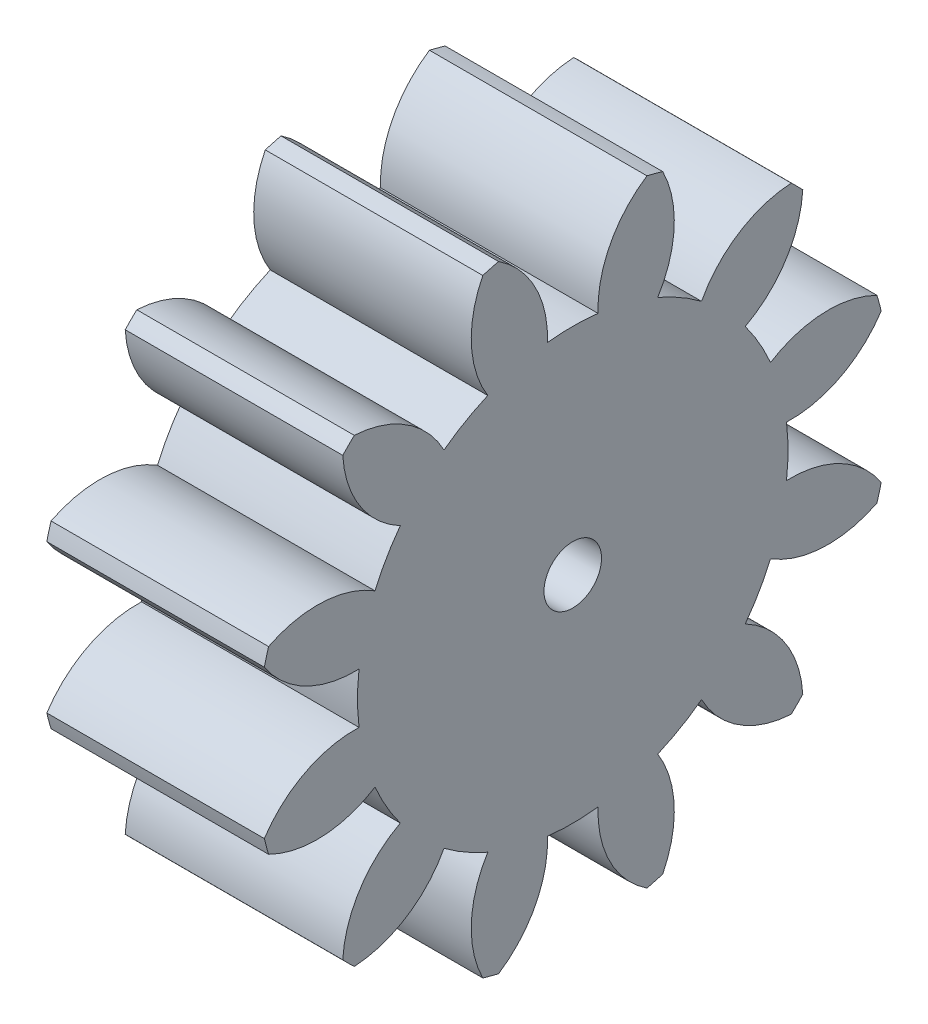
SolidWorks part; units mm, degrees
ref_plane "Plane1" through (0, 0, 0) normal (0, 0, 1) x (1, 0, 0)
ref_plane "Plane2" through (0, 0, 0) normal (0, 1, 0) x (1, 0, 0)
ref_plane "Plane3" through (0, 0, 0) normal (1, 0, 0) x (0, 0, -1)
other "Configuration Table"
sketch "HoldingSke" plane through (0, 0, 0) normal (0, 1, 0) x (1, 0, 0)
  line L0 (0, 0) -> (0.3913, -0.0832)
  line L1 (-15, 0) -> (100, 0) construction
  line L2 (0, 0) -> (-2.1039, 2.3779)
  line L3 (0, 0) -> (-11.863, 4.5341)
  line L4 (0, 0) -> (8.4473, 1.7955)
  line L5 (0, 0) -> (-46.8476, -17.4728)
  line L6 (0, 0) -> (-9.9476, -6.7116)
  line L7 (-2.1039, 2.3779) -> (8.6586, 51.2059)
  line L8 (-76.2, 54.61) -> (-75.7, 54.61)
  line L9 (-71.009, 38.7566) -> (-53.1078, 45.2721)
  line L10 (-76.2, 71.12) -> (104.1128, 71.12)
  line L11 (0, 0) -> (-12, 0)
  line L12 (-76.2, 101.6) -> (-76.113, 101.6)
  line L13 (24.9733, 27.94) -> (52.9518, 28.4284)
  line L14 (24.9733, 27.94) -> (24.9743, 27.94)
  line L15 (24.9733, 27.94) -> (100.4006, 29.5858)
  line L16 (-63.627, -2.5) -> (-12.827, -2.5)
  circle A0 centre (0, 0) radius 1.5
  circle A1 centre (0, 0) radius 11.874
  circle A2 centre (0, 0) radius 37.5
  circle A3 centre (0, 0) radius 1.5
  dimension "MHD" = 23.748
  dimension "Hub_dia" = 75
  dimension "Bore" = 3
  dimension "MBD" = 3
  dimension "Num_teeth" = 12
  dimension "Pitch" = 0.4
  dimension "Overall_len" = 50
  dimension "Show_teeth" = 12
  dimension "Thickness" = 12
  dimension "OAL" = 50.0001
  dimension "T_dim" = 0.5
  dimension "Ap" = 20
  dimension "H" = 19.05
  dimension "Pitch_radius" = 180.3128
  dimension "Width" = 12
  dimension "Backlash" = 0.087
  dimension "Addendum_fac" = 1
  dimension "Dedendum_fac" = 1.25
  dimension "Clearance_fac" = 0.25
  dimension "Dedendum_add" = 0.001
  dimension "Module" = 2.5
sketch "BasProSke" plane through (0, 0, 0) normal (0, 1, 0) x (1, 0, 0)
  line L0 (-10, 0) -> (60, 0) construction
  line L1 (0, 0) -> (0, 17.5)
  line L2 (0, 0) -> (12, 0)
  line L3 (12, 0) -> (12, 17.5)
  line L4 (12, 17.5) -> (0, 17.5)
  dimension "Thickness" = 12
  dimension "Diameter" = 35
revolve "Base-Revolve" add sketch "BasProSke" angle 360 about L0
sketch "TooCutSke" plane through (0, 0, 0) normal (1, 0, 0) x (0, 0, -1)
  line L1 (0, 0) -> (0, 107) construction
  line L2 (0, 0) -> (-2.1099, 14.8509) construction
  line L3 (0, 0) -> (-7.7081, 28.7671) construction
  line L4 (-2.1099, 14.8509) -> (-3.8541, 14.3835) construction
  arc A0 (1.3944, 11.7918) -> (-1.3944, 11.7918) centre (0, 0) ccw
  arc A1 (4.1219, 17.0338) -> (-4.1219, 17.0338) centre (0, 0) ccw
  circle A2 centre (0, 0) radius 15 construction
  circle A3 centre (0, 0) radius 14.0954 construction
  arc A4 (-1.3944, 11.7918) -> (-4.1219, 17.0338) centre (-7.3907, 12.0024) ccw
  arc A5 (4.1219, 17.0338) -> (1.3944, 11.7918) centre (7.3907, 12.0024) ccw
  dimension "Root_dia" = 23.748
  dimension "Overcut_dia" = 35.0508
  dimension "Pitch_dia" = 30
  dimension "Base_dia" = 28.1908
  dimension "Flank_rad" = 6
  dimension "Half_ang" = 15
  dimension "Half_CT" = 1.8056
extrude "ToothCut" cut sketch "TooCutSke" along normal through all
fillet "Breaks" [suppressed] radius 0.05
fillet "RootFillets" [suppressed] radius 0.626
pattern_circular "TeethCuts" count 12 every 30 about axis through (-10, 0, 0) along (1, 0, 0) of "ToothCut", "RootFillets", "Breaks"
sketch "HubNeaOneSke" plane through (0, 0, 0) normal (-1, 0, 0) x (0, 0, 1)
  circle A0 centre (0, 0) radius 11.874
  dimension "Diameter" = 23.748
extrude "HubNearOne" [suppressed] add sketch "HubNeaOneSke" along normal blind 38.0001
sketch "HubNeaBotSke" plane through (0, 0, 0) normal (-1, 0, 0) x (0, 0, 1)
  circle A0 centre (0, 0) radius 11.874
  dimension "Diameter" = 23.748
extrude "HubNearBoth" [suppressed] add sketch "HubNeaBotSke" along normal blind 19
ref_plane "FarPln" through (12, 0, 0) normal (1, 0, 0) x (0, 0, -1)
sketch "HubFarSke" plane through (12, 0, 0) normal (1, 0, 0) x (0, 0, -1)
  circle A0 centre (0, 0) radius 11.874
  dimension "Diameter" = 23.748
extrude "HubFar" [suppressed] add sketch "HubFarSke" along normal blind 19
sketch "BorSke" plane through (0, 0, 0) normal (1, 0, 0) x (0, 0, -1)
  circle A0 centre (0, 0) radius 1.5
  dimension "Diameter" = 3
extrude "Bore" cut sketch "BorSke" along normal mid plane 100.0001
sketch "KeySke" plane through (0, 0, 0) normal (1, 0, 0) x (0, 0, -1)
  line L0 (-0.6, 0) -> (-0.6, 2)
  line L1 (-0.6, 2) -> (0.6, 2)
  line L2 (0.6, 2) -> (0.6, 0)
  line L3 (0, 0) -> (0, 34) construction
  line L4 (-0.6, 0) -> (0.6, 0)
  dimension "Offset" = 2
extrude "Keyway" [suppressed] cut sketch "KeySke" along normal mid plane 100.0001
pattern_circular "Keyway2" [suppressed] count 2 every 90 about axis through (-10, 0, 0) along (1, 0, 0)
sketch "Croquis1" plane through (0, 0, 0) normal (-1, 0, 0) x (0, 0, 1)
  circle A0 centre (0, 0) radius 1.5875
  dimension "D1" = 3.175
extrude "Cortar-Extruir1" cut sketch "Croquis1" against normal through all
equation "' \"Module@HoldingSke\" = 6.35"
equation "' \"Num_teeth@HoldingSke\" = 12"
equation "' \"Ap@HoldingSke\" =  20"
equation "' \"Ap@HoldingSke\" = 20"
equation "' \"Width@HoldingSke\" = 0.5 * 25.4"
equation "' \"Hub_dia@HoldingSke\"= 1 * 25.4"
equation "' \"Hub_dia@HoldingSke\" = 1 * 25.4"
equation "' \"Overall_len@HoldingSke\" = 1.0 * 25.4"
equation "' \"Bore@HoldingSke\" = 0.75 * 25.4"
equation "' \"T_dim@HoldingSke\" = 0.1 * 25.4"
equation "' \"Width@KeySke\" = 0.25 * 25.4"
equation "' \"Show_teeth@HoldingSke\" = 13"
equation "' \"Backlash@HoldingSke\" = 0.009 * 25.4"
equation "' \"Addendum_fac@HoldingSke\" = 1.0"
equation "' \"Dedendum_fac@HoldingSke\" = 1.25"
equation "' \"Dedendum_add@HoldingSke\" = 0.00005 * 25.4"
equation "' \"Clearance_fac@HoldingSke\" = 0.25"
equation "\"Pitch@HoldingSke\" = 1 / \"Module@HoldingSke\""
equation "\"Overcut_dia@TooCutSke\" = (\"Num_teeth@HoldingSke\" + 2 * \"Addendum_fac@HoldingSke\") / \"Pitch@HoldingSke\" + 0.002 * 25.4"
equation "\"Pitch_dia@TooCutSke\" = \"Num_teeth@HoldingSke\" / \"Pitch@HoldingSke\""
equation "\"Base_dia@TooCutSke\" = \"Num_teeth@HoldingSke\" / \"Pitch@HoldingSke\" * cos((\"Ap@HoldingSke\"  * 3.14159265 / 180))"
equation "\"Root_dia@TooCutSke\" = (\"Num_teeth@HoldingSke\" + 2) / \"Pitch@HoldingSke\" - 2 * (\"Addendum_fac@HoldingSke\" + \"Dedendum_fac@HoldingSke\") / \"Pitch@HoldingSke\" - \"Dedendum_add@HoldingSke\" * 2"
equation "\"Half_ang@TooCutSke\" = 180 / \"Num_teeth@HoldingSke\""
equation "\"Half_CT@TooCutSke\" = \"Num_teeth@HoldingSke\" / \"Pitch@HoldingSke\" * sin((3.14159265 / 2 / \"Num_teeth@HoldingSke\")) / 2 - 7 * \"Backlash@HoldingSke\" / 4"
equation "\"Flank_rad@TooCutSke\" = \"Num_teeth@HoldingSke\" / \"Pitch@HoldingSke\" / 5"
equation "\"Radius@RootFillets\" = \"Clearance_fac@HoldingSke\" / \"Pitch@HoldingSke\" + \"Dedendum_add@HoldingSke\""
equation "\"Break_rad@Breaks\" = 0.02 / \"Pitch@HoldingSke\""
equation "\"Thickness@HoldingSke\" = \"Width@HoldingSke\""
equation "\"OAL@HoldingSke\" = \"Thickness@HoldingSke\""
equation "\"MHD@HoldingSke\" = (\"Num_teeth@HoldingSke\" + 2) / \"Pitch@HoldingSke\" - 2 * (\"Addendum_fac@HoldingSke\" + \"Dedendum_fac@HoldingSke\")  / \"Pitch@HoldingSke\" - \"Dedendum_add@HoldingSke\" * 2"
equation "\"MBD@HoldingSke\" = (\"Num_teeth@HoldingSke\" + 2) / \"Pitch@HoldingSke\" - 2 * (\"Addendum_fac@HoldingSke\" + \"Dedendum_fac@HoldingSke\")  / \"Pitch@HoldingSke\" - \"Dedendum_add@HoldingSke\" * 2 - 0.002 * 25.4"
equation "\"MHD@HoldingSke\" = ((sgn( \"MHD@HoldingSke\" - \"Hub_dia@HoldingSke\" )-1)*( \"MHD@HoldingSke\" - \"Hub_dia@HoldingSke\" ))/-2+ \"Hub_dia@HoldingSke\""
equation "\"MBD@HoldingSke\" = ((sgn( \"MBD@HoldingSke\" - \"Bore@HoldingSke\" )-1)*( \"MBD@HoldingSke\" - \"Bore@HoldingSke\" ))/-2+ \"Bore@HoldingSke\""
equation "\"OAL@HoldingSke\" = ((sgn( \"OAL@HoldingSke\" - \"Overall_len@HoldingSke\" )+1)*( \"OAL@HoldingSke\" - \"Overall_len@HoldingSke\" ))/2 + \"Overall_len@HoldingSke\" + 0.000002 * 25.4"
equation "\"Num_teeth@TeethCuts\" = int( \"Show_teeth@HoldingSke\" ) + 1"
equation "\"Num_teeth@TeethCuts\" = ((sgn( \"Num_teeth@TeethCuts\" - \"Num_teeth@HoldingSke\" )-1)*( \"Num_teeth@TeethCuts\" - \"Num_teeth@HoldingSke\" ))/-2+ \"Num_teeth@HoldingSke\""
equation "\"Num_teeth@TeethCuts\" = ((sgn( \"Num_teeth@TeethCuts\" - 2.0)+1)*( \"Num_teeth@TeethCuts\" - 2.0))/2 +2.0"
equation "\"Angle@TeethCuts\" = 360.0 / \"Num_teeth@HoldingSke\""
equation "\"Diameter@BasProSke\" = (\"Num_teeth@HoldingSke\" + 2 * \"Addendum_fac@HoldingSke\") / \"Pitch@HoldingSke\""
equation "\"Thickness@BasProSke\"  = \"Thickness@HoldingSke\""
equation "' \"Fillet_rad@BasProSke\" =  \"Thickness@HoldingSke\" * 0.05"
equation "' \"Fillet_rad@BasProSke\" = \"Thickness@HoldingSke\" * 0.05"
equation "\"MHD@HoldingSke\" = ((sgn( \"MHD@HoldingSke\" - \"Root_dia@TooCutSke\" )-1)*( \"MHD@HoldingSke\" - \"Root_dia@TooCutSke\" ))/-2+ \"Root_dia@TooCutSke\""
equation "\"Diameter@HubNeaOneSke\" = \"MHD@HoldingSke\""
equation "\"Length@HubNearOne\" = \"OAL@HoldingSke\" - \"Thickness@BasProSke\""
equation "\"Diameter@HubNeaBotSke\" = \"MHD@HoldingSke\""
equation "\"Length@HubNearBoth\" = ( \"OAL@HoldingSke\" - \"Thickness@BasProSke\" ) / 2.0"
equation "\"Thickness@FarPln\" = \"Thickness@BasProSke\""
equation "\"Diameter@HubFarSke\" = \"MHD@HoldingSke\""
equation "\"Length@HubFar\" = ( \"OAL@HoldingSke\" - \"Thickness@BasProSke\" ) / 2.0"
equation "\"Diameter@BorSke\" = \"MBD@HoldingSke\""
equation "\"D1@Bore\" = \"OAL@HoldingSke\" * 2.0"
equation "\"D1@Keyway\" = \"OAL@HoldingSke\" * 2.0"
equation "\"Offset@KeySke\" = \"T_dim@HoldingSke\" + \"MBD@HoldingSke\" / 2.0"
